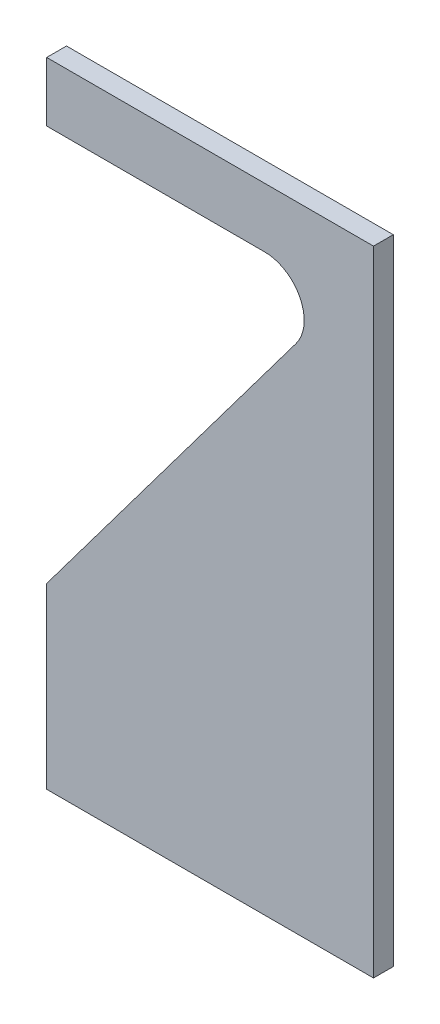
SolidWorks part; units mm, degrees
ref_plane "Front Plane" through (0, 0, 0) normal (0, 0, 1) x (1, 0, 0)
ref_plane "Top Plane" through (0, 0, 0) normal (0, 1, 0) x (1, 0, 0)
ref_plane "Right Plane" through (0, 0, 0) normal (1, 0, 0) x (0, 0, -1)
sketch "草图6" plane through (0, 0, 0) normal (0, 0, 1) x (1, 0, 0)
  line L0 (0, 0) -> (0, -320)
  line L1 (0, 0) -> (-165, 0)
  line L2 (-165, -30) -> (-54.9995, -30)
  line L3 (-38.9996, -62) -> (-165, -230)
  line L4 (-165, -230) -> (-165, -320)
  line L5 (-165, -320) -> (0, -320)
  line L6 (-165, 0) -> (-165, -30)
  arc A0 (-38.9996, -62) -> (-54.9995, -30) centre (-54.9995, -50) ccw
  dimension "D7" = 20
  dimension "D1" = 320
  dimension "D2" = 165
  dimension "D3" = 30
  dimension "D4" = 165
  dimension "D5" = 90
  dimension "D6" = 143.13
  dimension "D8" = 110.0005
  dimension "D9" = 210.0002
extrude "凸台-拉伸1" add sketch "草图6" along normal blind 10
